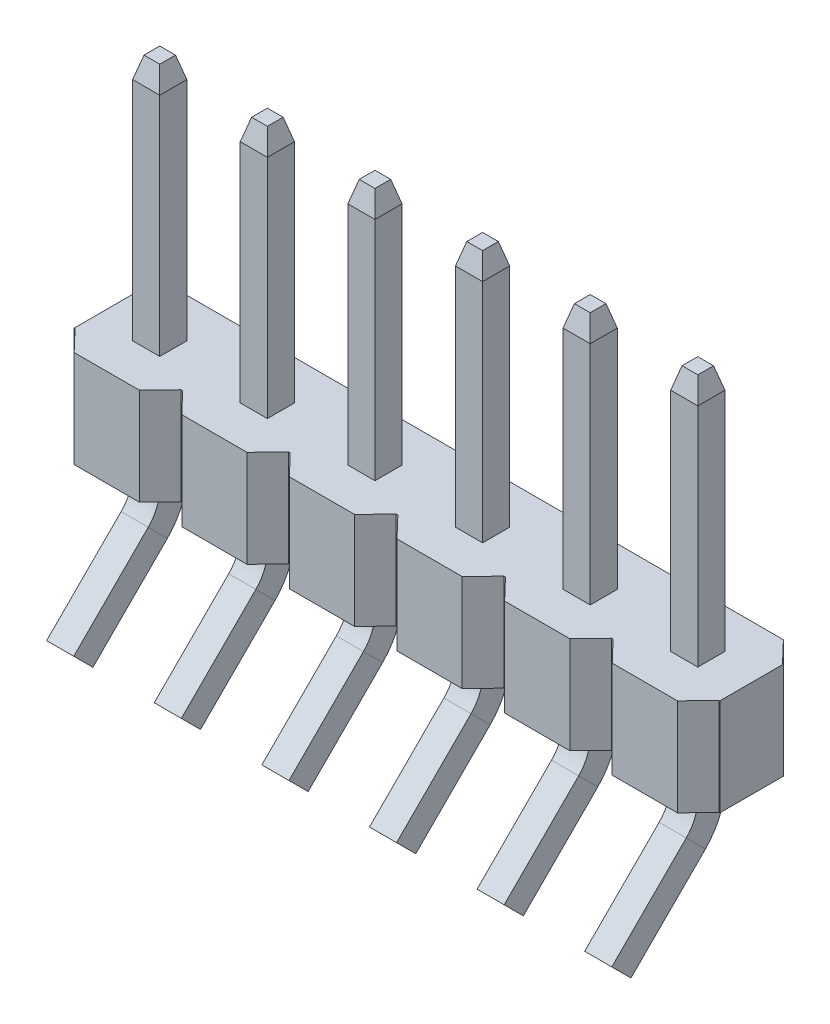
SolidWorks part; units mm, degrees
ref_plane "Front Plane" through (0, 0, 0) normal (0, 0, 1) x (1, 0, 0)
ref_plane "Top Plane" through (0, 0, 0) normal (0, 1, 0) x (1, 0, 0)
ref_plane "Right Plane" through (0, 0, 0) normal (1, 0, 0) x (0, 0, -1)
sketch "Sketch1" plane through (0, 0, 0) normal (0, 1, 0) x (1, 0, 0)
  line L14 (-0.77, 1.25) -> (0.77, 1.25)
  line L20 (-0.77, -1.25) -> (0.77, -1.25)
  line L22 (1.27, -0.75) -> (1.27, 0.75)
  line L23 (1.27, -1.25) -> (-1.27, 1.25) construction
  line L24 (0.77, -1.25) -> (1.25, -0.75)
  line L25 (1.25, -0.75) -> (1.27, -0.75)
  line L26 (0, 0) -> (0, -1.4708) construction
  line L27 (0, 0) -> (1.4893, 0) construction
  line L28 (0.77, 1.25) -> (1.25, 0.75)
  line L29 (1.25, 0.75) -> (1.27, 0.75)
  line L30 (-1.25, 0.75) -> (-1.27, 0.75)
  line L31 (-0.77, 1.25) -> (-1.25, 0.75)
  line L32 (-1.25, -0.75) -> (-1.27, -0.75)
  line L33 (-0.77, -1.25) -> (-1.25, -0.75)
  line L34 (-1.27, -0.75) -> (-1.27, 0.75)
  point P25 (0, 1.25)
  point P29 (0, 0)
  point P38 (1.27, 0)
  point P43 (0, -1.25)
  dimension "D11" = 1.25
  dimension "D12" = 1.27
  dimension "D13" = 0.5
  dimension "D14" = 0.02
  dimension "D15" = 0.5
extrude "Boss-Extrude1" add sketch "Sketch1" along normal blind 2.29
sketch "Sketch2" plane through (0, 0, 0) normal (1, 0, 0) x (0, 0, -1)
  line L0 (0, 8.13) -> (0, -0.4081)
  line L1 (-0.75, 2.29) -> (0.75, 2.29) construction
  line L2 (-0.3661, -1.292) -> (-2.1241, -3.05)
  line L3 (0.75, 0) -> (1.25, 0) construction
  arc A0 (0, -0.4081) -> (-0.3661, -1.292) centre (-1.25, -0.4081) cw
  dimension "D4" = 1.25
  dimension "D1" = 5.84
  dimension "D2" = 135
  dimension "D3" = 3.05
ref_plane "Plane1" through (0, 8.13, 0) normal (0, 1, 0) x (1, 0, 0)
sketch "Sketch3" plane through (0, 8.13, 0) normal (0, 1, 0) x (1, 0, 0)
  line L1 (-0.32, 0.32) -> (0.32, 0.32)
  line L2 (-0.32, 0.32) -> (-0.32, -0.32)
  line L3 (-0.32, -0.32) -> (0.32, -0.32)
  line L4 (0.32, 0.32) -> (0.32, -0.32)
  line L5 (-0.32, 0.32) -> (0.32, -0.32) construction
  line L6 (-0.32, -0.32) -> (0.32, 0.32) construction
  point P0 (0, 0)
  dimension "D1" = 0.64
sweep "Sweep1" add profiles "Sketch3" path "Sketch2"
chamfer "Chamfer3" distance 0.5 angle 15 4 edges at (0, 8.13, 0.32) (-0.32, 8.13, 0) (0, 8.13, -0.32) (0.32, 8.13, 0)
pattern_linear "LPattern1" count 6 spacing 2.54 along (1, 0, 0) of "Boss-Extrude1", "Sweep1", "Chamfer3"
